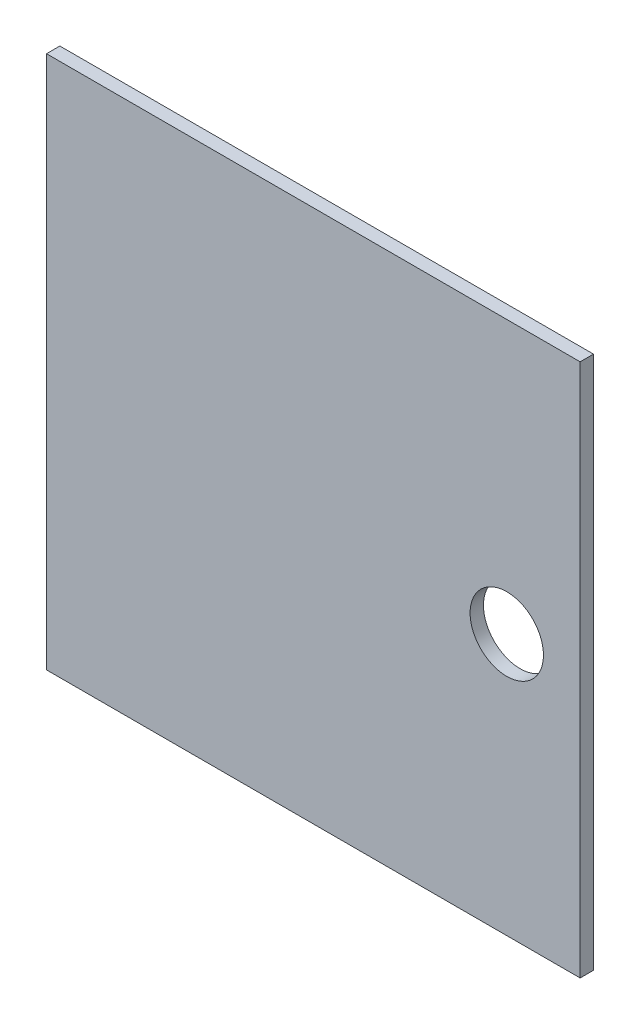
SolidWorks part; units mm, degrees
ref_plane "Front Plane" through (0, 0, 0) normal (0, 0, 1) x (1, 0, 0)
ref_plane "Top Plane" through (0, 0, 0) normal (0, 1, 0) x (1, 0, 0)
ref_plane "Right Plane" through (0, 0, 0) normal (1, 0, 0) x (0, 0, -1)
sketch "Sketch1" plane through (0, 0, 0) normal (0, 0, 1) x (1, 0, 0)
  line L1 (0, 0) -> (100, 0)
  line L2 (0, 0) -> (0, 100)
  line L3 (0, 100) -> (100, 100)
  line L4 (100, 0) -> (100, 100)
  dimension "D1" = 100
  dimension "D2" = 100
extrude "Boss-Extrude1" add sketch "Sketch1" along normal blind 2.5 contours L3 L4 L1 L2
sketch "Sketch2" plane through (0, 0, 2.5) normal (0, 0, 1) x (1, 0, 0)
  line L5 (0, 50) -> (12.5, 50) construction
  line L6 (0, 0) -> (0, 100) construction
  circle A1 centre (13.75, 50) radius 1.25
  dimension "D3" = 2.5
  dimension "D4" = 12.5
sketch "Sketch4" plane through (0, 0, 2.5) normal (0, 0, 1) x (1, 0, 0)
  line L0 (100, 50) -> (93.0433, 50) construction
  line L1 (100, 0) -> (100, 100) construction
  line L2 (86.25, 48.943) -> (43, 48.943) construction
  circle A0 centre (86.25, 48.943) radius 6.875
  point P7 (100, 50)
  dimension "D2" = 13.75
  dimension "D3" = 43.25
  dimension "D1" = 13.75
extrude "Cut-Extrude1" cut sketch "Sketch4" against normal through all
